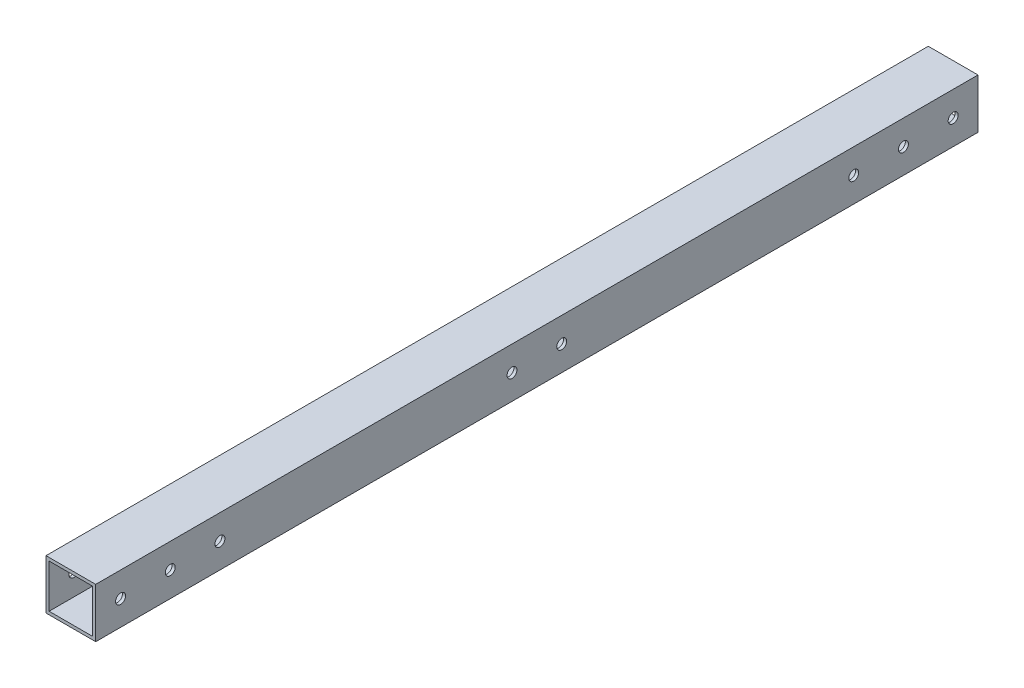
SolidWorks part; units mm, degrees
ref_plane "Front Plane" through (0, 0, 0) normal (0, 0, 1) x (1, 0, 0)
ref_plane "Top Plane" through (0, 0, 0) normal (0, 1, 0) x (1, 0, 0)
ref_plane "Right Plane" through (0, 0, 0) normal (1, 0, 0) x (0, 0, -1)
sketch "Sketch1" plane through (0, 0, 0) normal (0, 0, 1) x (1, 0, 0)
  line L1 (0, 0) -> (25.4, 0)
  line L2 (0, 0) -> (0, 25.4)
  line L3 (0, 25.4) -> (25.4, 25.4)
  line L4 (25.4, 0) -> (25.4, 25.4)
  line L5 (1.5875, 1.5875) -> (23.8125, 1.5875)
  line L6 (1.5875, 1.5875) -> (1.5875, 23.8125)
  line L7 (1.5875, 23.8125) -> (23.8125, 23.8125)
  line L8 (23.8125, 1.5875) -> (23.8125, 23.8125)
  dimension "D1" = 25.4
  dimension "D2" = 1.5875
  dimension "D3" = 1.5875
  dimension "D4" = 1.5875
  dimension "D5" = 1.5875
extrude "Boss-Extrude1" add sketch "Sketch1" along normal blind 450.85
sketch "Sketch4" plane through (25.4, 0, 0) normal (1, 0, 0) x (0, 0, -1)
  line L0 (-450.85, 25.4) -> (0, 25.4) construction
  line L1 (-450.85, 0) -> (-450.85, 25.4) construction
  line L2 (-225.425, 25.4) -> (-225.425, 0) construction
  line L3 (-450.85, 0) -> (0, 0) construction
  circle A0 centre (-438.15, 12.7) radius 2.54
  circle A14 centre (-412.75, 12.7) radius 2.54
  circle A15 centre (-387.35, 12.7) radius 2.54
  circle A16 centre (-63.5, 12.7) radius 2.54
  circle A17 centre (-38.1, 12.7) radius 2.54
  circle A18 centre (-12.7, 12.7) radius 2.54
  circle A19 centre (-238.125, 12.7) radius 2.54
  circle A20 centre (-212.725, 12.7) radius 2.54
  dimension "D1" = 5.08
  dimension "D2" = 12.7
  dimension "D3" = 12.7
  dimension "D4" = 3
  dimension "D5" = 12.7
extrude "Cut-Extrude3" cut sketch "Sketch4" against normal through all
